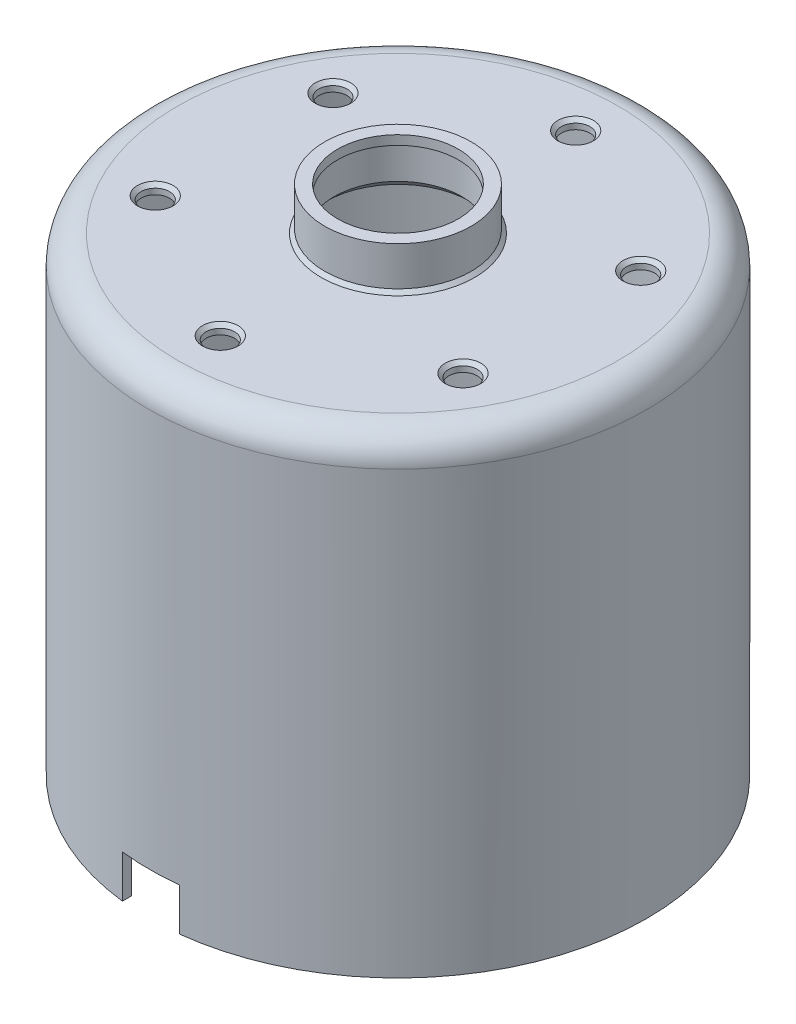
SolidWorks part; units mm, degrees
material "Free-Cutting Brass, UNS C36000"
ref_plane "Front" through (0, 0, 0) normal (0, 0, 1) x (1, 0, 0)
ref_plane "Top" through (0, 0, 0) normal (0, 1, 0) x (1, 0, 0)
ref_plane "Right" through (0, 0, 0) normal (1, 0, 0) x (0, 0, -1)
sketch "Sketch1" plane through (0, 0, 0) normal (0, 1, 0) x (1, 0, 0)
  circle A0 centre (0, 0) radius 17.5
  dimension "D1" = 35
extrude "Boss-Extrude1" add sketch "Sketch1" along normal blind 33
fillet "Fillet1" radius 2 1 edges at (0, 33, 17.5)
sketch "Sketch3" plane through (0, 33, 0) normal (0, 1, 0) x (1, 0, 0)
  circle A0 centre (0, 0) radius 5.15
  dimension "D1" = 10.3
extrude "Boss-Extrude2" add sketch "Sketch3" along normal blind 3
sketch "Sketch4" plane through (0, 36, 0) normal (0, 1, 0) x (1, 0, 0)
  circle A0 centre (0, 0) radius 4.25
  dimension "D1" = 8.5
chamfer "Chamfer1" distance 0.25 angle 45 1 edges at (0, 33, 5.15)
shell "Shell1" thickness 0.65
extrude "Cut-Extrude1" cut sketch "Sketch4" against normal up to next
sketch "Sketch5" plane through (0, 33, 0) normal (0, 1, 0) x (1, 0, 0)
  circle A0 centre (0, 12.5) radius 1
  dimension "D2" = 2
  dimension "D1" = 12.5
extrude "Cut-Extrude2" cut sketch "Sketch5" against normal up to next
chamfer "Chamfer2" distance 0.25 angle 45 1 edges at (0, 33, -11.5)
pattern_circular "CirPattern1" count 6 over 360 about axis through (0, 0, 0) along (0, 1, 0) of "Cut-Extrude2", "Chamfer2"
ref_plane "Plane1" through (0, 0, 17.5) normal (0, 0, 1) x (1, 0, 0)
sketch "Sketch6" plane through (0, 0, 17.5) normal (0, 0, 1) x (1, 0, 0)
  line L0 (-17.5, 0) -> (17.5, 0) construction
  line L1 (-2, -3) -> (2, -3)
  line L2 (-2, -3) -> (-2, 3)
  line L3 (-2, 3) -> (2, 3)
  line L4 (2, -3) -> (2, 3)
  line L5 (-2, -3) -> (2, 3) construction
  line L6 (-2, 3) -> (2, -3) construction
  point P0 (0, 0)
  dimension "D1" = 4
  dimension "D2" = 3
extrude "Cut-Extrude3" cut sketch "Sketch6" against normal up to next
